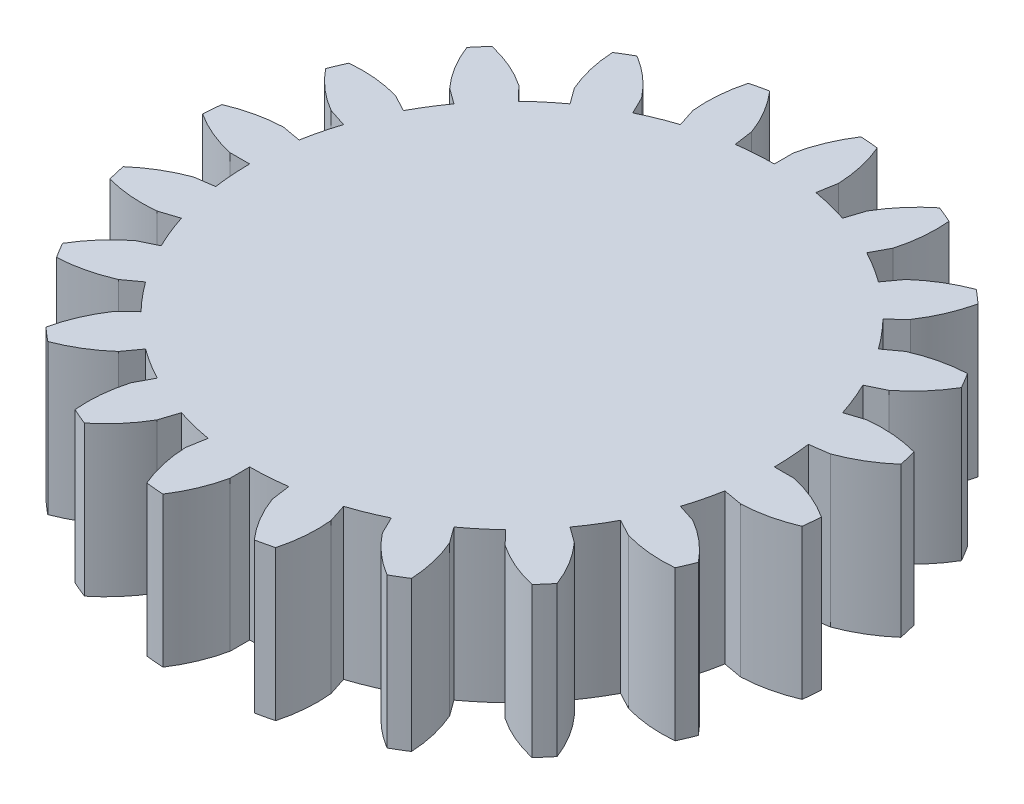
SolidWorks part; units mm, degrees
ref_plane "Front Plane" through (0, 0, 0) normal (0, 0, 1) x (1, 0, 0)
ref_plane "Top Plane" through (0, 0, 0) normal (0, 1, 0) x (1, 0, 0)
ref_plane "Right Plane" through (0, 0, 0) normal (1, 0, 0) x (0, 0, -1)
sketch "Sketch1" plane through (0, 0, 0) normal (0, 1, 0) x (1, 0, 0)
  circle A3 centre (0, 0) radius 8.75
  circle A4 centre (0, 0) radius 11
  circle A5 centre (0, 0) radius 10
  circle A6 centre (0, 0) radius 9
  circle A7 centre (0, 0) radius 9.3969
  dimension "pitch circle" = 20
  dimension "addendum circle" = 22
  dimension "root circle" = 17.5
  dimension "clearance circle" = 18
  dimension "base circle" = 18.7939
sketch "Sketch2" plane through (0, 0, 0) normal (0, 1, 0) x (1, 0, 0)
  line L0 (0, 0) -> (0, 9.3969)
  line L1 (0, 0) -> (4.6985, 8.138) construction
  line L2 (0, 0) -> (8.138, 4.6985) construction
  line L3 (0, 0) -> (9.3969, 0) construction
  line L4 (9.3969, 0) -> (9.3969, 14.7607) construction
  line L5 (8.138, 4.6985) -> (3.2178, 13.2205) construction
  line L6 (4.6985, 8.138) -> (0.4374, 10.5981) construction
  line L7 (0, 0) -> (3.0902, 9.5106)
  line L8 (0, 0) -> (1.5643, 9.8769) construction
  line L9 (0.8704, 9.962) -> (0, 0) construction
  circle A0 centre (0, 0) radius 9.3969 construction
  circle A1 centre (0, 0) radius 10 construction
  arc A2 (1.5643, 9.8769) -> (0.1723, 9.9985) centre (0, 0) ccw
  spline S0 degree 3 poles (0, 9.3969) (0.8266, 13.2451) (6.2259, 14.7657) (9.3969, 14.7607) knots 0 0 0 0 1 1 1 1
  spline S1 degree 3 poles (1.6297, 9.2545) (1.483, 13.1878) (-3.5708, 15.6216) (-6.6946, 16.1667) knots 0 0 0 0 1 1 1 1
  point P11 (0, 0)
  point P21 (0, 0)
  point P22 (0, 0)
  point P23 (0, 0)
  point P24 (0, 0)
  point P25 (0, 0)
  point P26 (0, 0)
  dimension "Involute Control" = 90
  dimension "Base circle quarter circumference" = 14.7607
  dimension "D1" = 9.8404
  dimension "D2" = 4.9202
  dimension "pitch circle" = 18
  dimension "Involute array" = 4
sketch "Sketch3" plane through (0, 0, 0) normal (0, 1, 0) x (1, 0, 0)
  line L0 (1.6297, 9.2545) -> (1.5175, 8.6174)
  line L1 (0, 0) -> (0, 9.3969) construction
  line L3 (0, 8.75) -> (0, 9.3969)
  arc A1 (0.6615, 10.9801) -> (0, 9.3969) centre (4.5797, 8.4132) ccw
  circle A2 centre (0, 0) radius 11 construction
  circle A3 centre (0, 0) radius 8.75 construction
  arc A7 (1.6297, 9.2545) -> (1.2528, 10.9284) centre (-3.0513, 9.0799) ccw
  arc A8 (1.5175, 8.6174) -> (0, 8.75) centre (0, 0) ccw
  arc A9 (1.2528, 10.9284) -> (0.6615, 10.9801) centre (0, 0) ccw
  circle A10 centre (0, 0) radius 9.3969 construction
  spline S0 degree 3 poles (1.6297, 9.2545) (1.483, 13.1878) (-3.5708, 15.6216) (-6.6946, 16.1667) knots 0 0 0 0 1 1 1 1 construction
  spline S1 degree 3 poles (0, 9.3969) (0.8266, 13.2451) (6.2259, 14.7657) (9.3969, 14.7607) knots 0 0 0 0 1 1 1 1 construction
  point P5 (1.4736, 8.3713)
  point P6 (0, 0)
  point P15 (0.5842, 8.4799)
  point P16 (0, 0)
  point P22 (1.723, 6.0078)
  point P24 (1.3461, 6.1033)
  point P25 (0, 6.9566)
  point P28 (0.0787, 6.2495)
  point P29 (0, 0)
  point P32 (0, 0)
  point P33 (0, 0)
  point P34 (1.4046, 6.0901)
extrude "Boss-Extrude1" add sketch "Sketch3" along normal blind 5
sketch "Sketch5" plane through (0, 0, 0) normal (1, 0, 0) x (0, 0, -1)
  line L0 (0, 0) -> (0, 5.4709) construction
pattern_circular "CirPattern4" count 20 over 360 about axis through (0, 0, 0) along (0, 1, 0) of bodies 101
sketch "Sketch6" plane through (0, 0, 0) normal (0, 1, 0) x (1, 0, 0)
  circle A0 centre (0, 0) radius 8.75 construction
  circle A1 centre (0, 0) radius 8.75
extrude "Boss-Extrude2" add sketch "Sketch6" along normal up to surface (5 mm away) up to face at (-9.4566, 5, 2.1843)
equation "\"Module\" = 1"
equation "\"Teeth number\"= 20"
equation "\"Pressure angle\"= 20deg"
equation "\"pitch circle@Sketch1\"= \"Module\" * \"Teeth number\""
equation "\"addendum circle@Sketch1\"= \"pitch circle@Sketch1\" + ( \"Module\" * 2 )"
equation "\"root circle@Sketch1\"= \"pitch circle@Sketch1\" - ( ( \"Module\" * 1.25 ) * 2 )"
equation "\"clearance circle@Sketch1\"= \"pitch circle@Sketch1\" - ( \"Module\" * 2 )"
equation "\"base circle@Sketch1\"= \"pitch circle@Sketch1\" * cos ( \"Pressure angle\" )"
equation "\"D1@Sketch2\"=\"Base circle quarter circumference@Sketch2\"/3*2"
equation "\"D2@Sketch2\"=\"Base circle quarter circumference@Sketch2\"/3"
equation "\"pitch circle@Sketch2\"=360/\"Teeth number\""
equation "\"D1@CirPattern4\"=\"Teeth number\""
equation "\"Base circle quarter circumference@Sketch2\"= \"base circle@Sketch1\" * pi / 4"
